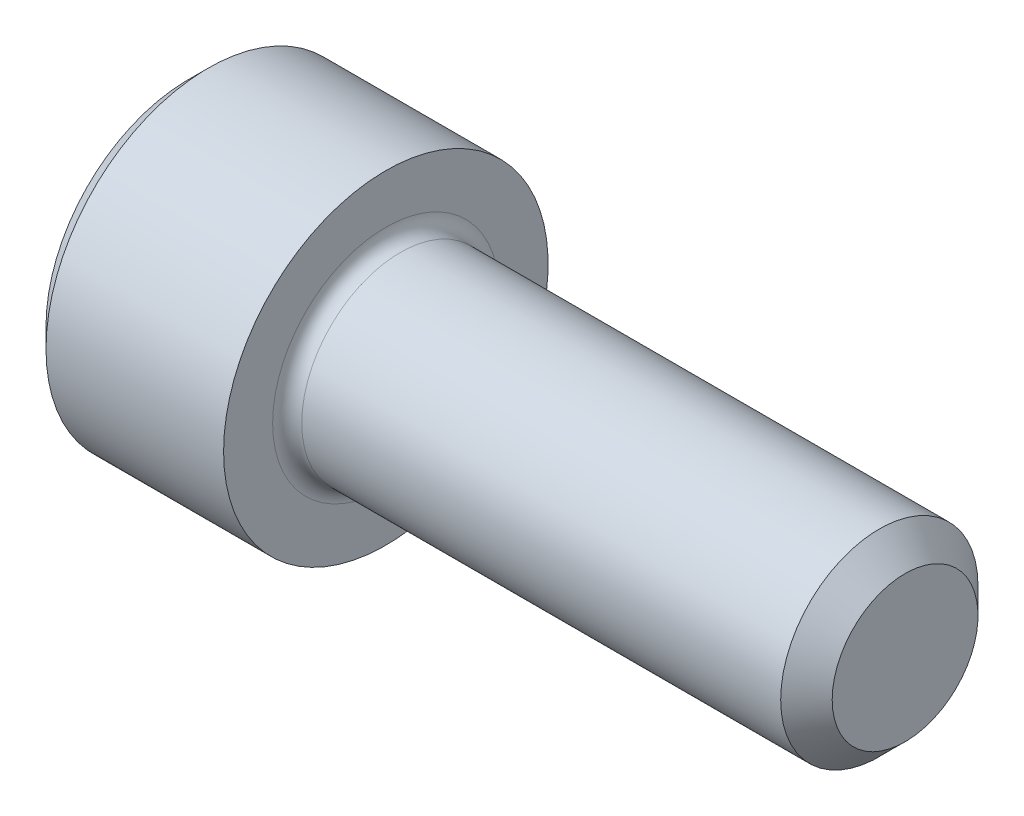
SolidWorks part; units mm, degrees
revolve "Base-Revolve" add sketch "BodySke"
sketch "BodySke" plane through (0, 0, 0) normal (0, 0, 1) x (1, 0, 0)
  line L0 (0, 0) -> (0, 3.4862)
  line L1 (0.4826, 3.9688) -> (4.826, 3.9688)
  line L2 (4.826, 3.9688) -> (4.826, 2.413)
  line L3 (4.826, 2.413) -> (16.8961, 2.413)
  line L4 (17.526, 1.7831) -> (17.526, 0)
  line L5 (17.526, 0) -> (0, 0)
  line L6 (-31.75, 0) -> (127, 0) construction
  line L7 (0, 3.4862) -> (0.4826, 3.9688)
  line L8 (17.526, 1.7831) -> (16.8961, 2.413)
  line L9 (0, -3.4862) -> (0.4826, -3.9688) construction
  line L10 (17.526, -1.7831) -> (16.8961, -2.413) construction
  line L11 (5.8852, 9.525) -> (5.8852, 3.175) construction
  line L12 (4.826, 9.525) -> (4.826, 3.175) construction
  line L13 (-20.574, 9.525) -> (-20.574, 3.175) construction
  dimension "Diameter" = 4.826
  dimension "Head_ht" = 4.826
  dimension "Length" = 12.7
  dimension "Body_ch_ang" = 45
  dimension "Head_dia" = 7.9375
  dimension "Head_ch_ang" = 45
  dimension "Head_side_ht" = 4.3434
  dimension "Minor_dia" = 3.5662
  dimension "Advance" = 1.0592
  dimension "Thread_nom" = 12.7
  dimension "Thread_length" = 38.1
cosmetic thread "ThreadCosmetic" [suppressed]
fillet "Fillet1" radius 0.3556 1 edges at (4.826, 0, 2.413)
ref_plane "Plane1" through (0, 0, 0) normal (0, 0, 1) x (1, 0, 0)
ref_plane "Plane2" through (0, 0, 0) normal (0, 1, 0) x (1, 0, 0)
ref_plane "Plane3" through (0, 0, 0) normal (1, 0, 0) x (0, 0, -1)
sketch "Sketch2" plane through (0, 0, 0) normal (0, 0, 1) x (1, 0, 0)
  line L0 (0, 1.985) -> (2.286, 1.985)
  line L1 (2.286, 1.985) -> (3.432, 0)
  line L2 (-31.75, 0) -> (127, 0) construction
  line L3 (3.432, 0) -> (0, 0)
  line L4 (0, 0) -> (0, 1.985)
  line L5 (0, 3.4862) -> (0, -3.4862) construction
  line L6 (0, 0) -> (47.625, 0) construction
  line L7 (4.826, -3.9688) -> (4.826, 3.9688) construction
  dimension "D1" = 1.985
  dimension "D2" = 60
revolve "Hex-PreBroach" cut sketch "Sketch2" angle 360 about L6
sketch "Sketch3" plane through (0, 0, 0) normal (-1, 0, 0) x (0, 0.5, 0.866)
  line L0 (1.146, 1.985) -> (-1.146, 1.985)
  line L1 (-1.146, 1.985) -> (-2.2921, 0)
  line L2 (1.146, 1.985) -> (2.2921, 0)
  line L3 (1.146, -1.985) -> (2.2921, 0)
  line L4 (1.146, -1.985) -> (-1.146, -1.985)
  line L5 (-1.146, -1.985) -> (-2.2921, 0)
  dimension "D1" = 1.985
  dimension "D2" = 1.985
  dimension "Hex_size" = 3.97
extrude "Hex" cut sketch "Sketch3" against normal blind 2.286
sketch "Sketch4" plane through (0, 0, 0) normal (-1, 0, 0) x (0, 0, 1)
  line L0 (0, 0) -> (2.3876, 0)
  line L1 (0, 0) -> (6.1484, 3.5498) construction
  line L2 (0, 0) -> (1.1938, 2.0677)
  line L3 (1.9883, 0.576) -> (2.2704, 0.7389)
  line L4 (1.493, 1.4339) -> (1.7751, 1.5968)
  arc A0 (1.9883, 0.576) -> (1.493, 1.4339) centre (0, 0) ccw
  arc A1 (2.3876, 0) -> (2.2704, 0.7389) centre (0, 0) ccw
  arc A2 (1.1938, 2.0677) -> (1.7751, 1.5968) centre (0, 0) cw
  dimension "D1" = 30
  dimension "D2" = 60
  dimension "Spline_p_dim" = 0.9906
  dimension "D3" = 0.4953
extrude "Spline" [suppressed] cut sketch "Sketch4" against normal blind 2.286
pattern_circular "CirPattern1" [suppressed] count 6 every 60
sketch "Sketch5" plane through (0, 0, 0) normal (0, 0, 1) x (1, 0, 0)
  line L0 (-31.75, 0) -> (127, 0) construction
  line L2 (0, 3.4862) -> (0, -3.4862) construction
  circle A0 centre (1.651, 0) radius 0.5906
  dimension "Drilled_hole_dia" = 1.1811
  dimension "Drilled_hole_loc" = 1.651
extrude "Hole" [suppressed] cut sketch "Sketch5" against normal through all and the other way through all
pattern_circular "Drilled-4" [suppressed] count 2 every 60
pattern_circular "Drilled-6" [suppressed] count 3 every 60
sketch "ThdSchSke" plane through (0, 0, 0) normal (0, 0, 1) x (1, 0, 0)
  line L0 (5.8852, -1.7831) -> (5.4441, -2.413)
  line L1 (5.8852, -1.7831) -> (6.3263, -2.413)
  line L2 (6.3263, -2.413) -> (6.3263, -3.0162)
  line L3 (-3.175, 0) -> (5.1513, 0) construction
  line L5 (6.3263, -3.0162) -> (5.4441, -3.0162)
  line L6 (5.4441, -3.0162) -> (5.4441, -2.413)
  line L7 (0, 3.4862) -> (0, -3.4862) construction
  dimension "Thread_minor" = 3.5662
  dimension "Diameter" = 4.826
  dimension "Start" = 5.8852
revolve "ThreadSchematic" [suppressed] cut sketch "ThdSchSke" angle 360 about L3
pattern_linear "ThdSchPat" [suppressed]
equation "\"D2@Sketch3\" = \"Hex_size@Sketch3\" / 2"
equation "\"D1@Sketch3\" = \"Hex_size@Sketch3\" / 2"
equation "\"D1@Sketch2\" = \"Hex_size@Sketch3\" / 2"
equation "\"D3@Sketch4\" = \"Spline_p_dim@Sketch4\" / 2"
equation "\"Thread_minor@ThreadCosmetic\"  =  \"Minor_dia@BodySke\""
equation "\"D2@CirPattern1\" = 360 / \"Num_teeth@CirPattern1\""
equation "\"Wall_thickness@Sketch2\" = \"Head_ht@BodySke\" - \"Key_eng@Hex\""
equation "\"Thread_length@ThreadCosmetic\" = ((sgn( (\"Length@BodySke\" - \"Advance@BodySke\" ) - \"Thread_nom@BodySke\" )-1)*( (\"Length@BodySke\" - \"Advance@BodySke\" ) - \"Thread_nom@BodySke\" ))/-2+ \"Thread_nom@BodySke\""
equation "\"Thread_minor@ThdSchSke\" = \"Minor_dia@BodySke\""
equation "\"Diameter@ThdSchSke\" = \"Diameter@BodySke\""
equation "\"Overcut@ThdSchSke\" = \"Diameter@BodySke\" * 1.25"
equation "\"Start@ThdSchSke\" = \"Head_ht@BodySke\" + \"Length@BodySke\" - \"Thread_length@ThreadCosmetic\"  '---Non-countersunk---"
equation "\"Num_threads@ThdSchPat\" = int( \"Thread_length@ThreadCosmetic\" / \"Advance@BodySke\" + 0.999 )  + 1"
equation "\"Advance@ThdSchPat\" = \"Thread_length@ThreadCosmetic\" /  (\"Num_threads@ThdSchPat\" - 1) 'relax it"
equation "\"Num_threads@ThdSchPat\" = \"Num_threads@ThdSchPat\" - sgn( \"Num_threads@ThdSchPat\" - 1) '---chamfered tips only---"
